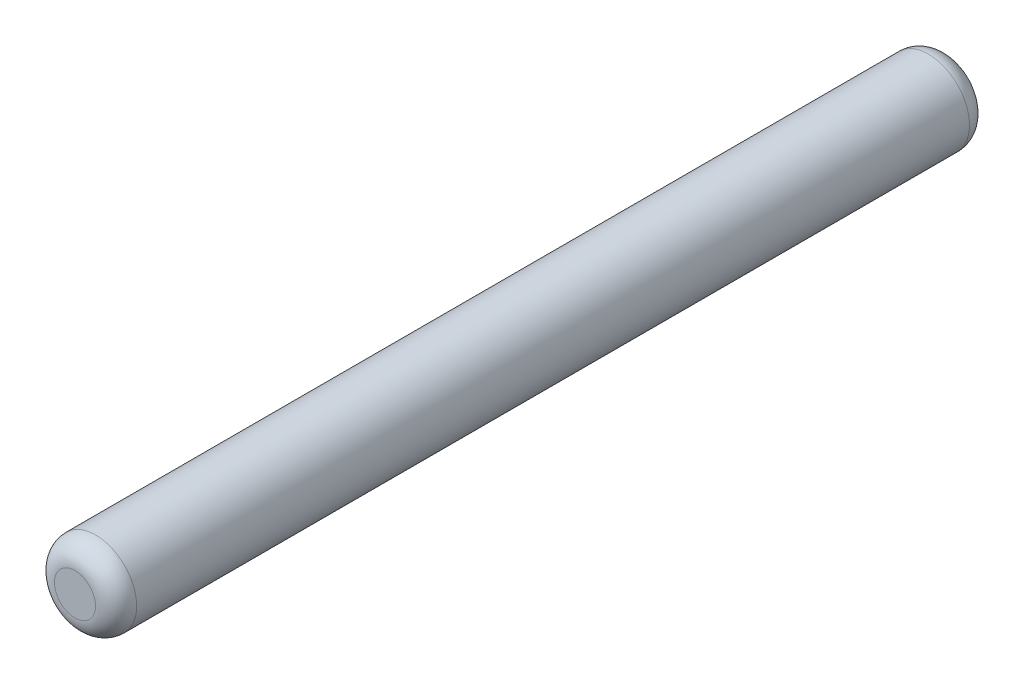
SolidWorks part; units mm, degrees
material "ABS"
ref_plane "正面" through (0, 0, 0) normal (0, 0, 1) x (1, 0, 0)
ref_plane "平面" through (0, 0, 0) normal (0, 1, 0) x (1, 0, 0)
ref_plane "右側面" through (0, 0, 0) normal (1, 0, 0) x (0, 0, -1)
sketch "ｽｹｯﾁ1" plane through (0, 0, 0) normal (0, 0, 1) x (1, 0, 0)
  circle A0 centre (0, 0) radius 2
  dimension "D1" = 4
extrude "ﾎﾞｽ - 押し出し1" add sketch "ｽｹｯﾁ1" along normal blind 42.5
fillet "ﾌｨﾚｯﾄ1" radius 1 2 edges at (2, 0, 0) (2, 0, 42.5)
